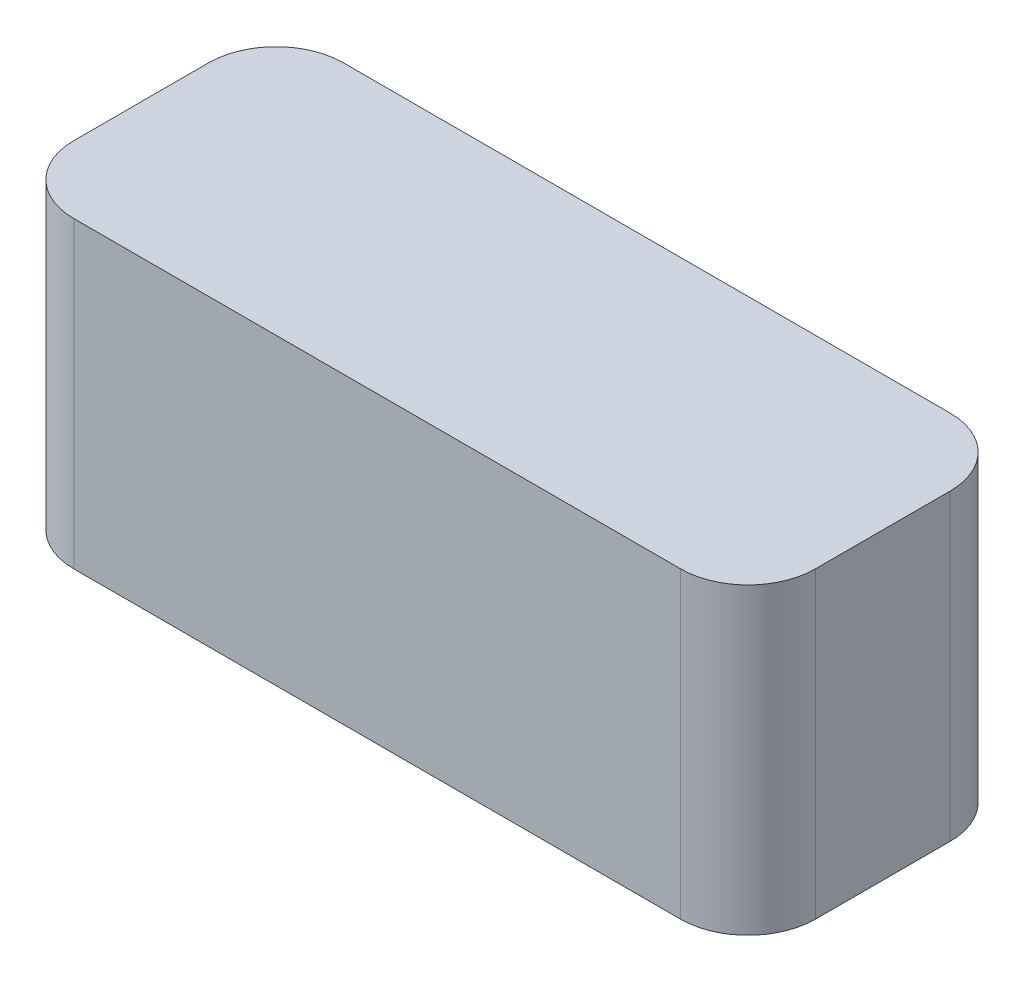
SolidWorks part; units mm, degrees
ref_plane "Front Plane" through (0, 0, 0) normal (0, 0, 1) x (1, 0, 0)
ref_plane "Top Plane" through (0, 0, 0) normal (0, 1, 0) x (1, 0, 0)
ref_plane "Right Plane" through (0, 0, 0) normal (1, 0, 0) x (0, 0, -1)
sketch "Esquisse1" plane through (0, 0, 0) normal (0, 0, 1) x (1, 0, 0)
  line L1 (0, 0) -> (110, 0)
  line L2 (0, 0) -> (0, 45)
  line L3 (0, 45) -> (110, 45)
  line L4 (110, 0) -> (110, 45)
  dimension "D1" = 45
  dimension "D2" = 110
extrude "Boss.-Extru.1" add sketch "Esquisse1" along normal blind 40
fillet "Congé1" radius 10 1 edges at (0, 22.5, 40)
fillet "Congé2" radius 10 1 edges at (110, 22.5, 40)
fillet "Congé3" radius 10 1 edges at (110, 22.5, 0)
fillet "Congé4" radius 10 1 edges at (0, 22.5, 0)
